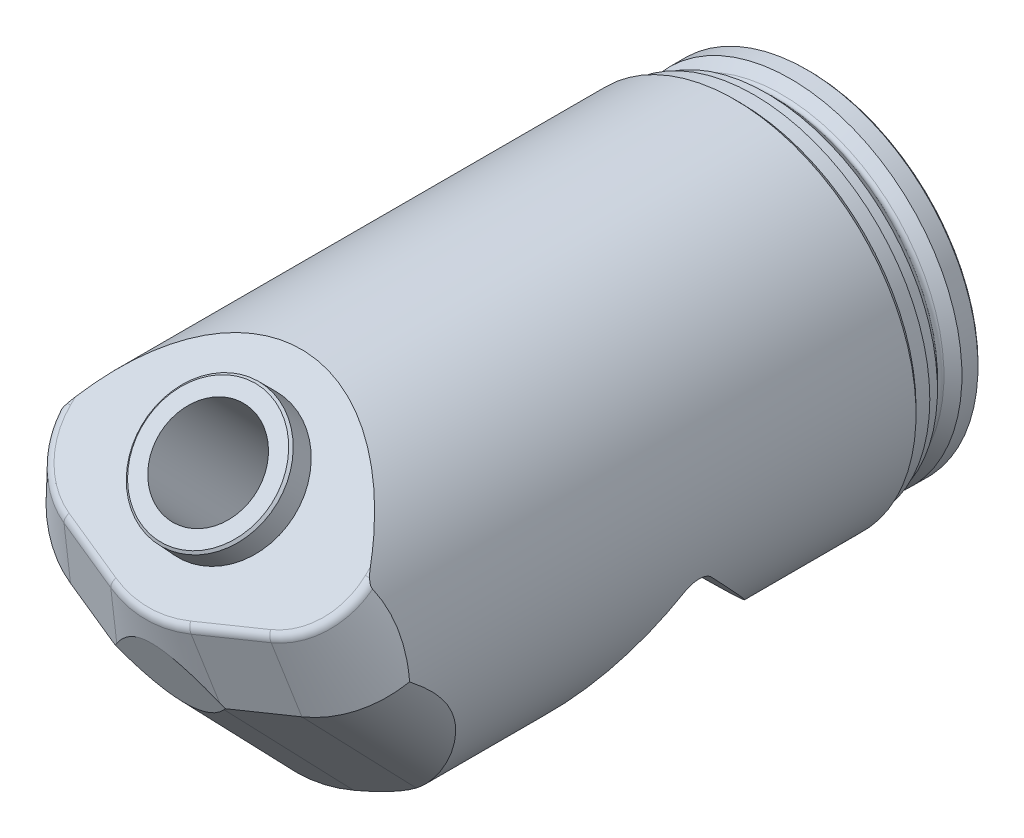
SolidWorks part; units mm, degrees
other "DetailItem1"
ref_plane "front" through (0, 0, 0) normal (0, 0, 1) x (1, 0, 0)
ref_plane "top" through (0, 0, 0) normal (0, 1, 0) x (1, 0, 0)
ref_plane "right" through (0, 0, 0) normal (1, 0, 0) x (0, 0, -1)
sketch "L2D-00 Layout" plane through (0, 0, 0) normal (1, 0, 0) x (0, 0, -1)
  line L0 (-101.1889, 5.0927) -> (-75.1375, 30.1625) construction
  line L1 (27.7667, 0) -> (-53.34, 0) construction
  line L2 (-3.2385, 30.1625) -> (-2.286, 29.21)
  line L3 (0, 28.448) -> (2.032, 28.448)
  line L4 (9.144, 28.448) -> (9.144, 23.8125)
  line L5 (-3.2385, 30.1625) -> (-101.1889, 30.1625)
  line L6 (-101.1889, 30.1625) -> (-101.1889, 0)
  line L7 (-101.1889, 0) -> (-21.039, 0)
  line L8 (-2.286, 29.21) -> (0, 29.21)
  line L9 (0, 29.21) -> (0, 28.448)
  line L10 (9.144, 23.8125) -> (-6.731, 23.8125)
  line L11 (-3.2385, -30.1625) -> (-101.1889, -30.1625)
  line L12 (0, -29.21) -> (0, -28.448)
  line L13 (-2.286, -29.21) -> (0, -29.21)
  line L14 (0, -28.448) -> (2.032, -28.448)
  line L15 (-3.2385, -30.1625) -> (-2.286, -29.21)
  line L17 (-81.743, 23.8059) -> (-46.5182, -12.7981)
  line L18 (-87.4624, 18.302) -> (-52.2376, -18.302) construction
  line L19 (-6.731, 23.8125) -> (-21.039, 0)
  line L20 (-36.3095, -7.3804) -> (-14.3859, -30.1625)
  line L21 (-46.5182, -12.7981) -> (-40.7988, -7.2942)
  line L22 (-21.039, 0) -> (-6.731, -23.8125)
  line L23 (-6.731, -23.8125) -> (9.144, -23.8125)
  line L24 (-101.1889, 0) -> (-101.1889, -30.1625)
  line L25 (9.144, -23.8125) -> (9.144, -28.448)
  line L26 (9.144, 23.8125) -> (9.144, -23.8125)
  line L27 (-98.138, -7.2354) -> (-76.0748, -30.1625)
  line L28 (-98.138, -7.2354) -> (-101.1889, 5.0927)
  line L29 (6.096, 28.448) -> (4.6028, 26.9548)
  line L30 (3.5252, 26.9548) -> (2.032, 28.448)
  line L31 (6.096, 28.448) -> (9.144, 28.448)
  line L32 (6.096, -28.448) -> (4.6028, -26.9548)
  line L33 (3.5252, -26.9548) -> (2.032, -28.448)
  line L34 (6.096, -28.448) -> (9.144, -28.448)
  arc A0 (4.6028, 26.9548) -> (3.5252, 26.9548) centre (4.064, 27.4936) cw
  arc A1 (4.6028, -26.9548) -> (3.5252, -26.9548) centre (4.064, -27.4936) ccw
  arc A2 (-40.7988, -7.2942) -> (-36.3095, -7.3804) centre (-38.5973, -9.582) cw
  point P5 (-69.85, 0)
  point P45 (-38.5111, -5.0927)
  dimension "D1" = 46.1
  dimension "D2" = 60.325
  dimension "D26" = 45
  dimension "D29" = 0.762
  dimension "D30" = 3.175
  dimension "D3" = 56.896
  dimension "D4" = 19.05
  dimension "D5" = 45
  dimension "D6" = 87.4624
  dimension "D7" = 0.762
  dimension "D8" = 2.286
  dimension "D9" = 59
  dimension "D10" = 36.1548
  dimension "D11" = 9.144
  dimension "D12" = 19.05
  dimension "D13" = 15.875
  dimension "D14" = 50.8
  dimension "D15" = 25.4
  dimension "D16" = 17.1048
  dimension "D17" = 43.9
  dimension "D18" = 38.1
  dimension "D19" = 15.875
  dimension "D20" = 47.625
  dimension "D21" = 4.6355
  dimension "D22" = 110.3329
  dimension "D23" = 69.85
  dimension "D24" = 30
  dimension "D25" = 25.4
  dimension "D27" = 4.064
  dimension "D28" = 3.048
  dimension "D31" = 25.4
  dimension "D32" = 69.85
ref_plane "RPL-00 Plane for notch." through (0, -18.302, 52.2376) normal (0, -0.7206, -0.6934) x (1, 0, 0)
sketch "Sketch3" plane through (0, 0, 0) normal (1, 0, 0) x (0, 0, -1)
  line L0 (27.7667, 0) -> (-53.34, 0) construction
  line L1 (-101.1889, 30.1625) -> (-101.1889, 0) construction
  line L2 (-3.2385, 30.1625) -> (-101.1889, 30.1625) construction
  line L3 (-3.2385, 30.1625) -> (-2.286, 29.21) construction
  line L4 (-2.286, 29.21) -> (0, 29.21) construction
  line L5 (0, 29.21) -> (0, 28.448) construction
  line L6 (0, 28.448) -> (2.032, 28.448) construction
  line L7 (3.5252, 26.9548) -> (2.032, 28.448) construction
  line L8 (27.7667, 0) -> (-53.34, 0) construction
  line L19 (6.096, 28.448) -> (4.6028, 26.9548) construction
  line L20 (6.096, 28.448) -> (9.144, 28.448) construction
  line L21 (9.144, 28.448) -> (9.144, 23.8125) construction
  line L22 (9.144, 23.8125) -> (-6.731, 23.8125) construction
  line L23 (-6.731, 23.8125) -> (-21.039, 0) construction
  line L24 (-101.1889, 30.1625) -> (-101.1889, 0)
  line L25 (-3.2385, 30.1625) -> (-101.1889, 30.1625)
  line L26 (-3.2385, 30.1625) -> (-2.286, 29.21)
  line L27 (-2.286, 29.21) -> (0, 29.21)
  line L28 (0, 29.21) -> (0, 28.448)
  line L29 (0, 28.448) -> (2.032, 28.448)
  line L30 (3.5252, 26.9548) -> (2.032, 28.448)
  line L31 (6.096, 28.448) -> (4.6028, 26.9548)
  line L32 (6.096, 28.448) -> (9.144, 28.448)
  line L33 (9.144, 28.448) -> (9.144, 23.8125)
  line L34 (9.144, 23.8125) -> (-6.731, 23.8125)
  line L35 (-6.731, 23.8125) -> (-21.039, 0)
  line L36 (-101.1889, 0) -> (-21.039, 0) construction
  line L37 (-101.1889, 0) -> (-21.039, 0)
  arc A0 (3.5252, 26.9548) -> (4.6028, 26.9548) centre (4.064, 27.4936) ccw construction
  arc A1 (3.5252, 26.9548) -> (4.6028, 26.9548) centre (4.064, 27.4936) ccw
revolve "FBR-00 Basic blank revolve." add sketch "Sketch3" angle 360 about L8
sketch "Sketch13" plane through (0, 0, 0) normal (1, 0, 0) x (0, 0, -1)
  line L0 (-60.0094, 44.7206) -> (-79.3063, 26.1508)
  line L1 (-79.3063, 26.1508) -> (-82.534, 29.3898)
  line L2 (-82.534, 29.3898) -> (-90.6326, 21.5964)
  line L3 (-90.6326, 21.5964) -> (-105.0748, 36.604)
  line L4 (-105.0748, 36.604) -> (-77.6218, 63.0226)
  line L5 (-77.6218, 63.0226) -> (-60.0094, 44.7206)
  line L6 (-105.0748, 36.604) -> (-113.2648, 45.1146) construction
  line L7 (-87.4624, 18.302) -> (-52.2376, -18.302) construction
  dimension "D1" = 91
  dimension "D2" = 38.1
  dimension "D3" = 4.572
  dimension "D4" = 22.479
  dimension "D5" = 25.4
  dimension "D7" = 22.6386
revolve "FCR-00 lacation boss, Cut-Revolve." cut sketch "Sketch13" angle 360 about L6
hole_wizard "41/64 (0.640630) Diameter Hole1" positions "Sketch15" profile "Sketch14" hole size "41/64" standard "Ansi Inch" end condition through all
sketch "Sketch15" plane through (0, 56.4956, 54.3669) normal (0, 0.7206, 0.6934) x (1, 0, 0)
  point P0 (0, -50.3305)
sketch "Sketch14" plane through (0, 21.5964, 90.6326) normal (1, 0, 0) x (0, -0.6934, 0.7206)
  line L0 (0, 0) -> (0, 106.4802)
  line L1 (0, 106.4802) -> (8.136, 106.4802)
  line L2 (8.136, 106.4802) -> (8.136, 0)
  line L5 (8.136, 0) -> (0, 0)
  line L11 (0, -6.35) -> (0, 107.95) construction
  dimension "Thru Hole Dia." = 16.272
  dimension "Thru Hole Depth" = 106.4802
sketch "Sketch6" plane through (0, 53.2013, 51.1967) normal (0, 0.7206, 0.6934) x (1, 0, 0)
  line L1 (-6.5155, -68.2316) -> (-17.0437, -64.3997)
  line L2 (0, -50.3305) -> (0, -38.0293) construction
  line L3 (0, -69.3805) -> (0, -33.2257) construction
  line L4 (-25.4, -52.4656) -> (-25.4, -39.7656)
  arc A0 (-6.5155, -68.2316) -> (0, -69.3805) centre (0, -50.3305) ccw
  arc A1 (-17.0437, -64.3997) -> (-25.4, -52.4656) centre (-12.7, -52.4656) cw
  point P13 (-25.4, -61.3582)
  dimension "D3" = 25.4
  dimension "D2" = 19.05
  dimension "D4" = 12.7
  dimension "D1" = 70
  dimension "D5" = 12.7
sketch "Sketch16" plane through (0, 117.7716, -110.9823) normal (-1, 0, 0) x (0, -0.9982, -0.0593)
  line L0 (112.3848, 216.1659) -> (136.58, 195.5013) construction
  line L1 (112.3848, 216.1659) -> (99.8974, 218.4803) construction
  line L2 (152.3072, 182.069) -> (168.8032, 201.3833)
  line L3 (168.8032, 201.3833) -> (110.8603, 250.8712)
  line L4 (110.8603, 250.8712) -> (88.1783, 224.314)
  line L6 (112.3848, 216.1659) -> (152.3072, 182.069)
  line L7 (112.3848, 216.1659) -> (100.7986, 218.3133)
  line L8 (99.3022, 217.7834) -> (97.8354, 216.066)
  line L9 (97.8354, 216.066) -> (88.1783, 224.314)
  arc A0 (100.7986, 218.3133) -> (99.3022, 217.7834) centre (100.5093, 216.7524) ccw
  dimension "D1" = 1.5875
  dimension "D2" = 25.4
  dimension "D3" = 76.2
  dimension "D4" = 12.7
  dimension "D5" = 34.925
sweep "FCS-00 End trim, Cut-Sweep" cut profiles "Sketch16" path "Sketch6"
mirror "FMR-00 Mirror end trim." about plane through (0, 0, 0) normal (1, 0, 0) of "FCS-00 End trim, Cut-Sweep"
sketch "Sketch7" plane through (0, -18.302, 52.2376) normal (0, -0.7206, -0.6934) x (1, 0, 0)
  line L0 (0, 0) -> (0, 38.1) construction
  line L1 (15.123, -8.7312) -> (38.4948, 31.75) construction
  line L2 (38.4948, 31.75) -> (-38.4948, 31.75)
  line L3 (-38.4948, 31.75) -> (-15.123, -8.7312) construction
  line L4 (38.4948, 31.75) -> (38.4948, -19.05)
  line L5 (38.4948, -19.05) -> (-38.4948, -19.05)
  line L6 (-38.4948, -19.05) -> (-38.4948, 31.75)
  line L8 (0, -13.7482) -> (11.9063, -6.8741) construction
  line L9 (11.9063, -6.8741) -> (11.9063, 6.8741) construction
  line L10 (11.9063, 6.8741) -> (0, 13.7482) construction
  line L11 (0, 13.7482) -> (-11.9062, 6.8741) construction
  line L12 (-11.9062, 6.8741) -> (-11.9062, -6.8741) construction
  line L13 (-11.9062, -6.8741) -> (0, -13.7482) construction
  circle A0 centre (0, 0) radius 16.6687 construction
  arc A1 (-15.123, -8.7312) -> (15.123, -8.7312) centre (0, 0) ccw construction
  circle A2 centre (0, 0) radius 11.9062 construction
  point P10 (0, 31.75)
  dimension "D2" = 19.05
  dimension "D4" = 17.4625
  dimension "D6" = 33.3375
  dimension "D1" = 38.1
  dimension "D3" = 60
  dimension "D5" = 31.75
  dimension "D7" = 23.8125
extrude "FCE-00 Bolt head notch." cut sketch "Sketch7" along normal blind 50.8
fillet "Fillet1" radius 3.175 1 edges at (0, -5.0927, 38.5111)
chamfer "Chamfer1" distance 0.381 angle 45 3 edges at (-28.448, 0, -9.144) (-23.8125, 0, -9.144) (0, 29.3898, 82.534)
sketch "Sketch17" plane through (0, 0, 0) normal (1, 0, 0) x (0, 0, -1)
  line L0 (-107.2947, 15.33) -> (-88.0965, -24.2072)
  line L1 (-101.1889, 5.0927) -> (-75.1375, 30.1625) construction
  dimension "D1" = 26.9875
  dimension "D2" = 108
extrude "Cut-Extrude1" cut sketch "Sketch17" against normal through all and the other way through all flip side to cut
sketch "Sketch18" plane through (0, -39.2342, 80.7997) normal (0, -0.4368, 0.8996) x (1, 0, 0)
  text T0 "1" font "SWRomns" height 6.35
sketch "Sketch10" plane through (0, 0, 0) normal (0, 1, 0) x (1, 0, 0)
  line L0 (0, 38.5125) -> (0, -115.1189)
extrude "FCE-00 Section." [suppressed] cut sketch "Sketch10" against normal through all and the other way through all
